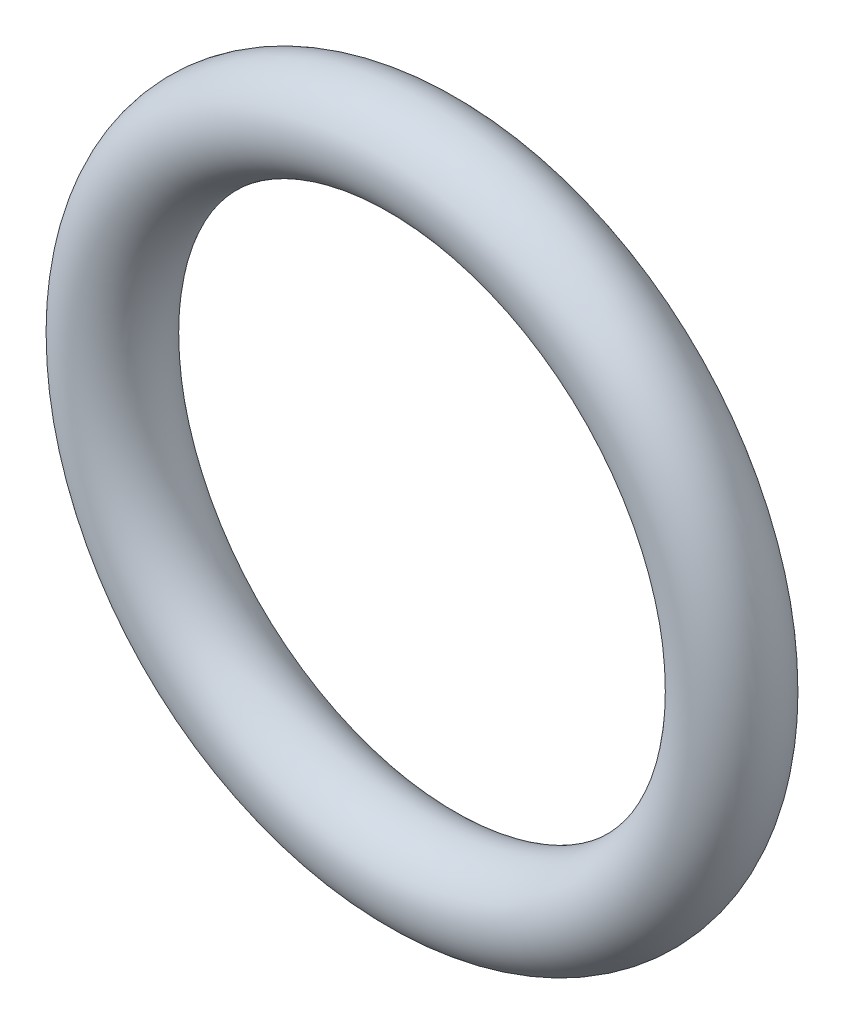
SolidWorks part; units mm, degrees
ref_plane "Front Plane" through (0, 0, 0) normal (0, 0, 1) x (1, 0, 0)
ref_plane "Top Plane" through (0, 0, 0) normal (0, 1, 0) x (1, 0, 0)
ref_plane "Right Plane" through (0, 0, 0) normal (1, 0, 0) x (0, 0, -1)
sketch "Sketch1" plane through (0, 0, 0) normal (1, 0, 0) x (0, 0, -1)
  line L0 (0, 0) -> (3.6818, 0) construction
  circle A0 centre (0, 8.25) radius 1.25
  dimension "D1" = 2.5
  dimension "D2" = 8.25
revolve "Revolve1" add sketch "Sketch1" angle 360 about L0
sketch "Sketch2" plane through (0, 0, 0) normal (0, 0, 1) x (1, 0, 0)
  circle A0 centre (0, 0) radius 4.0527 construction
ref_plane "Plane1" through (0, 0, 0.7) normal (0, 0, 1) x (1, 0, 0)
